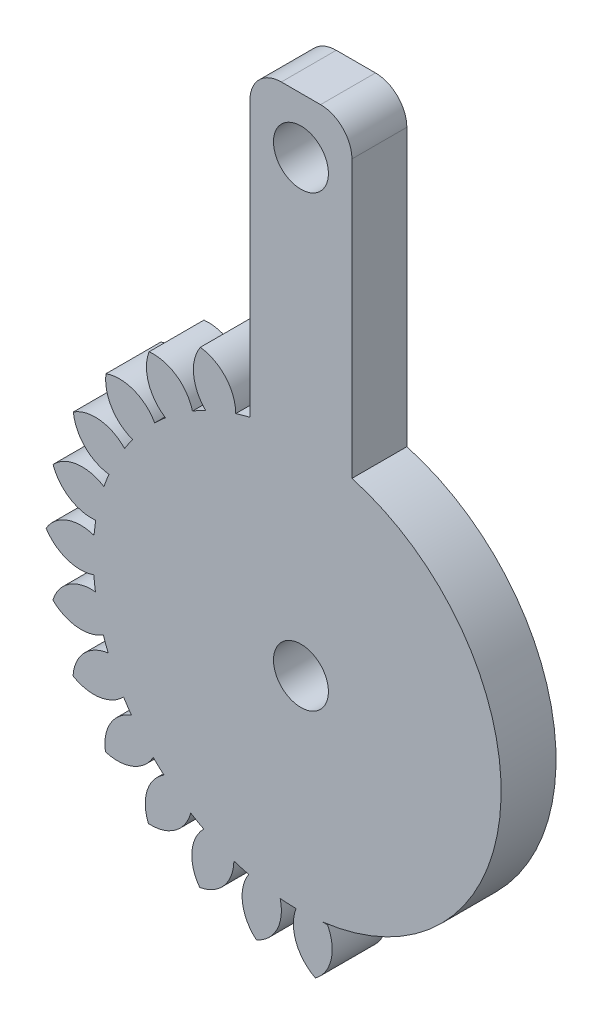
SolidWorks part; units mm, degrees
ref_plane "Front Plane" through (0, 0, 0) normal (0, 0, 1) x (1, 0, 0)
ref_plane "Top Plane" through (0, 0, 0) normal (0, 1, 0) x (1, 0, 0)
ref_plane "Right Plane" through (0, 0, 0) normal (1, 0, 0) x (0, 0, -1)
ref_plane "Plane1" through (0, 0, 5) normal (0, 0, 1) x (1, 0, 0)
ref_plane "Plane3" through (0, 0, 3) normal (0, 0, 1) x (1, 0, 0)
sketch "Sketch1" plane through (0, 0, 5) normal (0, 0, 1) x (1, 0, 0)
  circle A0 centre (0, 20.9252) radius 3.9726
  circle A1 centre (0, 20.9252) radius 5
  dimension "D1" = 10
sketch "Sketch5" plane through (0, 0, 3) normal (0, 0, 1) x (1, 0, 0)
  circle A0 centre (0, 20.9252) radius 13
extrude "Boss-Extrude3" add sketch "Sketch5" along normal blind 3.5 contours A0
sketch "Sketch6" plane through (0, 0, 3) normal (0, 0, 1) x (1, 0, 0)
  line L1 (-3.01, 33.0817) -> (3.49, 33.0817)
  line L2 (-3.01, 33.0817) -> (-3.01, 53.0817)
  line L3 (-3.01, 53.0817) -> (3.49, 53.0817)
  line L4 (3.49, 33.0817) -> (3.49, 53.0817)
  dimension "D1" = 20
  dimension "D2" = 6.5
extrude "Boss-Extrude4" add sketch "Sketch6" along normal up to surface (3.5 mm away) up to face at (13, 20.9252, 6.5)
sketch "Sketch9" plane through (0, 0, 3) normal (0, 0, -1) x (-1, 0, 0)
  line L0 (-0.24, 53.0817) -> (-0.24, 49.0919) construction
  line L1 (-3.49, 53.0817) -> (3.01, 53.0817) construction
  line L2 (-0.24, 47.7817) -> (-0.24, -3.3539) construction
  line L3 (-13, 20.9252) -> (46.8577, 20.9252) construction
  circle A0 centre (-0.24, 49.5317) radius 1.75
  arc A1 (-3.49, 33.448) -> (3.01, 33.572) centre (0, 20.9252) ccw construction
  circle A2 centre (-0.24, 20.9252) radius 1.75
  dimension "D1" = 3.55
extrude "Cut-Extrude1" cut sketch "Sketch9" against normal up to surface (3.5 mm away) up to face at (0.118, 36.9003, 6.5)
fillet "Fillet1" radius 2 2 edges at (3.49, 53.0817, 4.75) (-3.01, 53.0817, 4.75)
ref_plane "Plane4" through (0, 0, 15) normal (0, 0, 1) x (1, 0, 0)
sketch "Sketch10" plane through (0, 0, 3) normal (0, 0, 1) x (1, 0, 0)
  line L0 (-5.7594, 32.4645) -> (-3.9194, 33.1775)
  line L1 (0.24, 53.0817) -> (0.24, -3.388) construction
  line L3 (13, 20.9252) -> (-7.0281, 20.9252) construction
  line L20 (-8.2588, 30.7699) -> (-6.6328, 31.8881)
  line L21 (-10.3, 28.5446) -> (-8.9758, 30.0076)
  line L22 (-11.7731, 25.9085) -> (-10.8219, 27.6375)
  line L23 (-12.5985, 23.0038) -> (-12.0717, 24.9055)
  line L24 (-12.7318, 19.987) -> (-12.6577, 21.9589)
  line L25 (-12.1657, 17.0208) -> (-12.5485, 18.9567)
  line L26 (-10.9309, 14.2651) -> (-11.7498, 16.0605)
  line L27 (-9.0939, 11.8684) -> (-10.3047, 13.4266)
  line L28 (-6.7536, 9.96) -> (-8.2911, 11.197)
  line L29 (-4.0364, 8.6427) -> (-5.8177, 9.4918)
  line L30 (-1.0886, 7.9876) -> (-3.0177, 8.403)
  line L31 (1.9309, 8.03) -> (-0.042, 7.9892)
  arc A0 (-3.9194, 33.1775) -> (-6.1748, 35.8519) centre (-6.4822, 33.3045) ccw
  arc A3 (-6.1748, 35.8519) -> (-5.7594, 32.4645) centre (-4.0035, 34.399) ccw
  arc A53 (-6.6328, 31.8881) -> (-9.4442, 33.9702) centre (-9.1558, 31.4205) ccw
  arc A54 (-9.4442, 33.9702) -> (-8.2588, 30.7699) centre (-6.9964, 33.0572) ccw
  arc A55 (-8.9758, 30.0076) -> (-12.1916, 31.3853) centre (-11.323, 28.9708) ccw
  arc A56 (-12.1916, 31.3853) -> (-10.3, 28.5446) centre (-9.5992, 31.0614) ccw
  arc A57 (-10.8219, 27.6375) -> (-14.2687, 28.2364) centre (-12.8667, 26.0873) ccw
  arc A58 (-14.2687, 28.2364) -> (-11.7731, 25.9085) centre (-11.6715, 28.5191) ccw
  arc A59 (-12.0717, 24.9055) -> (-15.5637, 24.6934) centre (-13.7039, 22.9256) ccw
  arc A60 (-15.5637, 24.6934) -> (-12.5985, 23.0038) centre (-13.1017, 25.5674) ccw
  arc A61 (-12.6577, 21.9589) -> (-16.0067, 20.9472) centre (-13.7893, 19.656) ccw
  arc A62 (-16.0067, 20.9472) -> (-12.7318, 19.987) centre (-13.8126, 22.3655) ccw
  arc A63 (-12.5485, 18.9567) -> (-15.5739, 17.1999) centre (-13.1185, 16.4548) ccw
  arc A64 (-15.5739, 17.1999) -> (-12.1657, 17.0208) centre (-13.766, 19.0859) ccw
  arc A65 (-11.7498, 16.0605) -> (-14.2885, 13.6534) centre (-11.7274, 13.4946) ccw
  arc A66 (-14.2885, 13.6534) -> (-10.9309, 14.2651) centre (-12.9643, 15.9055) ccw
  arc A67 (-10.3047, 13.4266) -> (-12.2199, 10.4989) centre (-9.6912, 10.9351) ccw
  arc A68 (-12.2199, 10.4989) -> (-9.0939, 11.8684) centre (-11.4507, 12.9957) ccw
  arc A69 (-8.2911, 11.197) -> (-9.4795, 7.9065) centre (-7.1197, 8.9141) ccw
  arc A70 (-9.4795, 7.9065) -> (-6.7536, 9.96) centre (-9.3069, 10.5134) ccw
  arc A71 (-5.8177, 9.4918) -> (-6.2152, 6.016) centre (-4.1513, 7.5406) ccw
  arc A72 (-6.2152, 6.016) -> (-4.0364, 8.6427) centre (-6.6484, 8.5924) ccw
  arc A73 (-3.0177, 8.403) -> (-2.6029, 4.9292) centre (-0.9462, 6.8887) ccw
  arc A74 (-2.6029, 4.9292) -> (-1.0886, 7.9876) centre (-3.6186, 7.3362) ccw
  arc A75 (-0.042, 7.9892) -> (1.1627, 4.7047) centre (2.3228, 6.9935) ccw
  arc A76 (1.1627, 4.7047) -> (1.9309, 8.03) centre (-0.3808, 6.8127) ccw
  point P26 (0.24, 20.9252)
  point P78 (0.24, 20.9252)
  point P153 (0.24, 20.9252)
  dimension "D1" = 13
extrude "Boss-Extrude5" add sketch "Sketch10" along normal up to surface (3.5 mm away) up to face at (1.99, 49.5317, 6.5)
